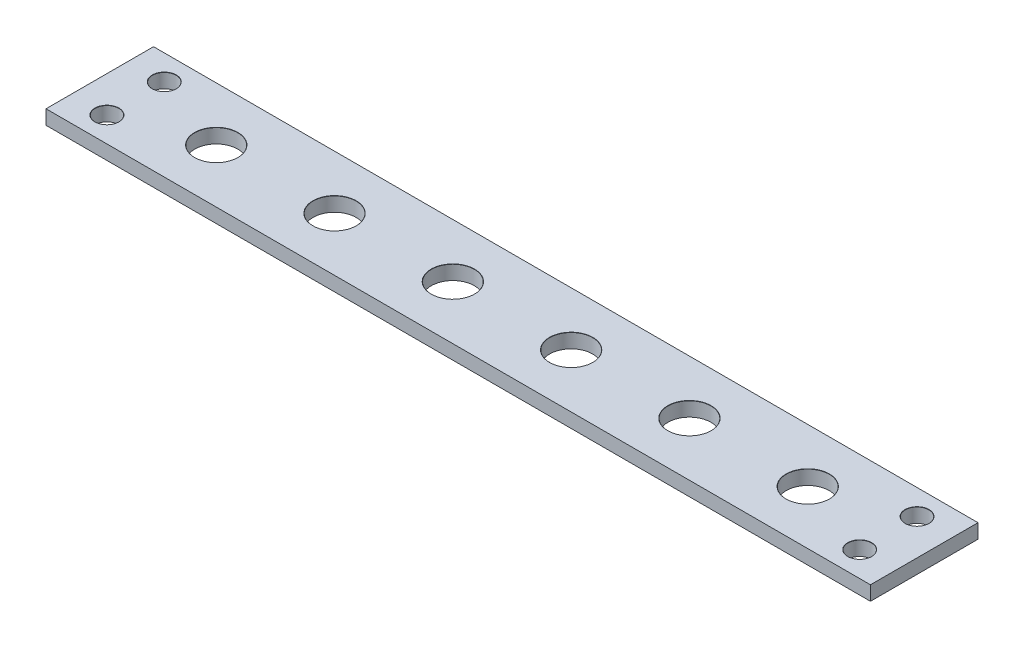
SolidWorks part; units mm, degrees
material "1060 Alloy"
ref_plane "Front Plane" through (0, 0, 0) normal (0, 0, 1) x (1, 0, 0)
ref_plane "Top Plane" through (0, 0, 0) normal (0, 1, 0) x (1, 0, 0)
ref_plane "Right Plane" through (0, 0, 0) normal (1, 0, 0) x (0, 0, -1)
sketch "Sketch1" plane through (0, 0, 0) normal (0, 1, 0) x (1, 0, 0)
  line L1 (-57.5, 7.5) -> (57.5, 7.5)
  line L2 (-57.5, 7.5) -> (-57.5, -7.5)
  line L3 (-57.5, -7.5) -> (57.5, -7.5)
  line L4 (57.5, 7.5) -> (57.5, -7.5)
  line L5 (-57.5, 7.5) -> (57.5, -7.5) construction
  line L6 (-57.5, -7.5) -> (57.5, 7.5) construction
  point P0 (0, 0)
  dimension "D1" = 15
  dimension "D2" = 115
extrude "Boss-Extrude1" add sketch "Sketch1" along normal blind 2
hole_wizard "Ø3.3 (3.3) Diameter Hole1" positions "Sketch3" profile "Sketch4" hole size "Ø3.3" standard "ISO"
sketch "Sketch3" plane through (0, 2, 0) normal (0, 1, 0) x (1, 0, 0)
  line L0 (-52.5, 0) -> (52.5, 0) construction
  line L1 (-52.5, 4) -> (-52.5, -4) construction
  line L3 (52.5, 4) -> (52.5, -4) construction
  point P11 (-52.5, 4)
  point P12 (-52.5, -4)
  point P15 (52.5, 4)
  point P16 (52.5, -4)
  dimension "D1" = 105
  dimension "D2" = 8
  dimension "D3" = 8
sketch "Sketch4" plane through (52.5, 2, 4) normal (1, 0, 0) x (0, 0, 1)
  line L0 (0, 0) -> (0, 15.9914)
  line L1 (0, 15.9914) -> (1.65, 15)
  line L2 (1.65, 15) -> (1.65, 0.025)
  line L3 (1.65, 0.025) -> (1.675, 0)
  line L5 (1.675, 0) -> (0, 0)
  line L6 (-1.65, 0.025) -> (-1.675, 0) construction
  line L10 (0, 15.9914) -> (-1.65, 15) construction
  line L11 (0, -6.35) -> (0, 107.95) construction
  dimension "Hole Dia." = 3.3
  dimension "Hole Depth" = 15
  dimension "Near C'Sink Dia." = 3.35
  dimension "Near C'Sink Angle" = 90
  dimension "Drill Angle" = 118
hole_wizard "Ø6.0 (6) Diameter Hole1" positions "Sketch5" profile "Sketch6" hole size "Ø6.0" standard "ISO"
sketch "Sketch5" plane through (0, 2, 0) normal (0, 1, 0) x (1, 0, 0)
  line L0 (8.25, 0) -> (-8.25, 0) construction
  line L1 (0, 0) -> (0, -7.5) construction
  line L2 (-57.5, -7.5) -> (57.5, -7.5) construction
  line L4 (8.25, 0) -> (24.75, 0) construction
  line L5 (24.75, 0) -> (41.25, 0) construction
  point P0 (-8.25, 0)
  point P2 (8.25, 0)
  point P8 (24.75, 0)
  point P10 (41.25, 0)
  point P12 (-24.75, 0)
  point P14 (-41.25, 0)
  dimension "D1" = 16.5
sketch "Sketch6" plane through (-8.25, 2, 0) normal (1, 0, 0) x (0, 0, 1)
  line L0 (0, 0) -> (0, 16.8026)
  line L1 (0, 16.8026) -> (3, 15)
  line L2 (3, 15) -> (3, 0.025)
  line L3 (3, 0.025) -> (3.025, 0)
  line L5 (3.025, 0) -> (0, 0)
  line L6 (-3, 0.025) -> (-3.025, 0) construction
  line L10 (0, 16.8026) -> (-3, 15) construction
  line L11 (0, -6.35) -> (0, 107.95) construction
  dimension "Hole Dia." = 6
  dimension "Hole Depth" = 15
  dimension "Near C'Sink Dia." = 6.05
  dimension "Near C'Sink Angle" = 90
  dimension "Drill Angle" = 118
